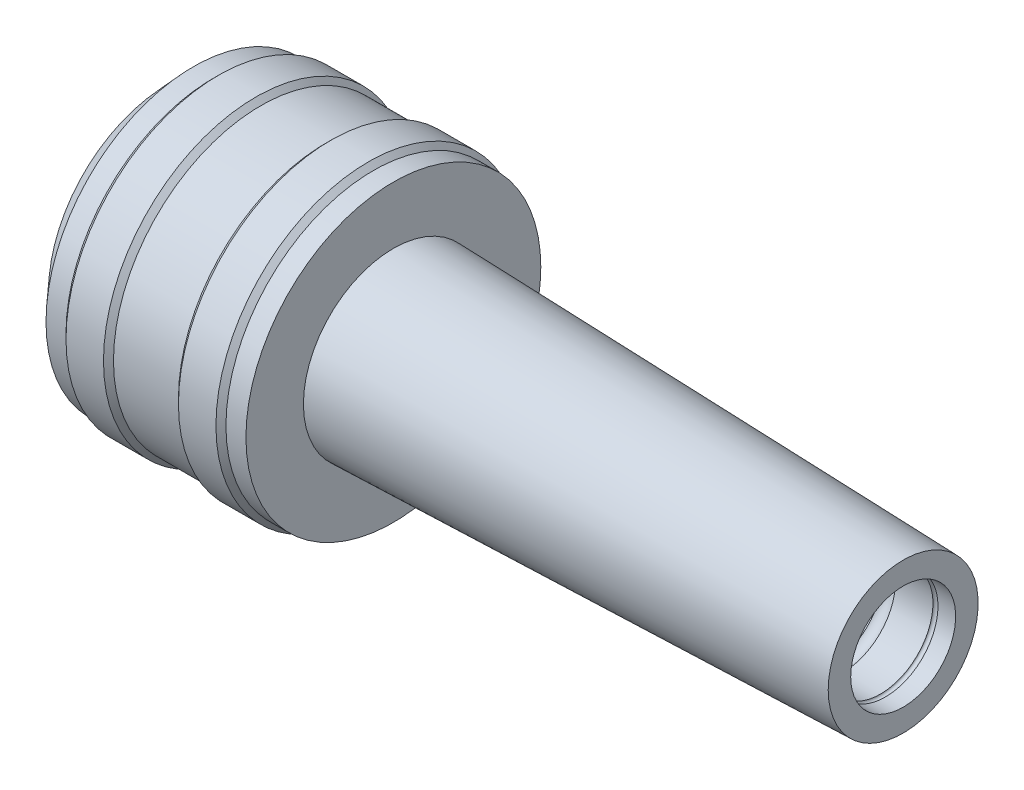
SolidWorks part; units mm, degrees
material "Plain Carbon Steel"
ref_plane "Front Plane" through (0, 0, 0) normal (0, 0, 1) x (1, 0, 0)
ref_plane "Top Plane" through (0, 0, 0) normal (0, 1, 0) x (1, 0, 0)
ref_plane "Right Plane" through (0, 0, 0) normal (1, 0, 0) x (0, 0, -1)
sketch "Sketch1" plane through (0, 0, 0) normal (0, 0, 1) x (1, 0, 0)
  line L0 (-185.1611, 0) -> (227.0562, 0) construction
  line L1 (-69.541, 59) -> (-61.541, 59)
  line L2 (-59.541, 61) -> (-44.541, 61)
  line L3 (-61.541, 59) -> (-59.541, 61)
  line L4 (-44.541, 61) -> (-42.541, 59)
  line L5 (-16.541, 59) -> (-14.541, 61)
  line L6 (2.459, 59) -> (0.459, 61)
  line L7 (-14.541, 61) -> (0.459, 61)
  line L8 (-42.541, 59) -> (-16.541, 59)
  line L9 (2.459, 59) -> (10.459, 59)
  line L10 (-69.541, 59) -> (-79.541, 48)
  line L11 (-79.541, 48) -> (-33.541, 48)
  line L12 (-33.541, 48) -> (-33.541, 49.6573)
  line L13 (-33.541, 49.6573) -> (-29.541, 49.6573)
  line L14 (-29.541, 49.6573) -> (-29.541, 42)
  line L15 (-29.541, 42) -> (-1.541, 42)
  line L16 (-1.541, 42) -> (-1.541, 21)
  line L17 (-1.541, 21) -> (185.3782, 21)
  line L18 (190.3782, 21) -> (205.3782, 21)
  line L19 (207.3782, 21) -> (214.459, 21)
  line L20 (10.459, 59) -> (10.459, 36)
  line L21 (214.459, 21) -> (214.459, 30)
  line L22 (214.459, 30) -> (10.459, 36)
  arc A0 (185.3782, 21) -> (190.3782, 21) centre (187.8782, 18.5) cw
  arc A2 (205.3782, 21) -> (207.3782, 21) centre (206.3782, 20.6972) cw
  dimension "D21" = 17
  dimension "D1" = 59
  dimension "D2" = 61
  dimension "D3" = 15
  dimension "D4" = 2
  dimension "D5" = 2
  dimension "D6" = 2
  dimension "D7" = 2
  dimension "D8" = 15
  dimension "D9" = 30
  dimension "D10" = 10
  dimension "D11" = 10
  dimension "D12" = 10
  dimension "D13" = 48
  dimension "D14" = 4
  dimension "D15" = 30
  dimension "D16" = 42
  dimension "D17" = 28
  dimension "D18" = 21
  dimension "D19" = 5
  dimension "D20" = 2
  dimension "D22" = 7.0808
  dimension "D23" = 294
  dimension "D24" = 36
  dimension "D25" = 30
revolve "Revolve1" add sketch "Sketch1" angle 360 about L0
